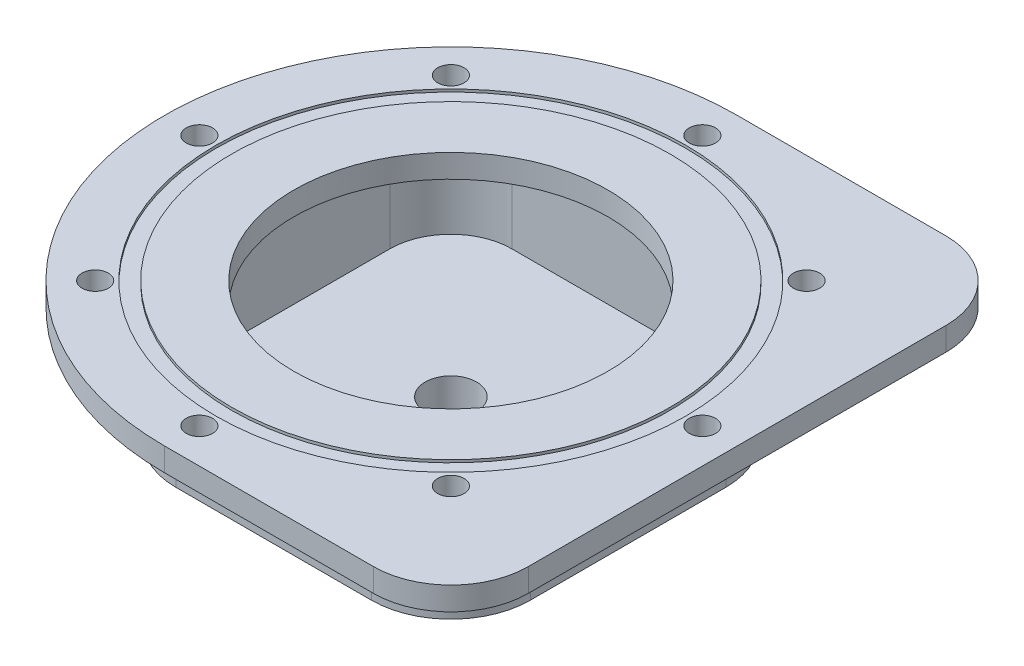
SolidWorks part; units mm, degrees
ref_plane "Front" through (0, 0, 0) normal (0, 0, 1) x (1, 0, 0)
ref_plane "Top" through (0, 0, 0) normal (0, 1, 0) x (1, 0, 0)
ref_plane "Right" through (0, 0, 0) normal (1, 0, 0) x (0, 0, -1)
sketch "Sketch1" plane through (0, 0, 0) normal (0, 1, 0) x (1, 0, 0)
  circle A2 centre (0, 0) radius 38.5318
  circle A3 centre (0, 0) radius 35.9918
  dimension "D1" = 77.0636
  dimension "D2" = 71.9836
sketch "Sketch2" plane through (0, 0, 0) normal (0, 1, 0) x (1, 0, 0)
  line L7 (34.29, 46.99) -> (-34.29, 46.99)
  line L8 (46.99, 34.29) -> (46.99, -34.29)
  line L9 (34.29, -46.99) -> (-34.29, -46.99)
  line L10 (-46.99, 34.29) -> (-46.99, -34.29)
  line L11 (46.99, 46.99) -> (-46.99, -46.99) construction
  line L12 (46.99, -46.99) -> (-46.99, 46.99) construction
  arc A3 (-34.29, -46.99) -> (-46.99, -34.29) centre (-34.29, -34.29) cw
  arc A4 (34.29, 46.99) -> (46.99, 34.29) centre (34.29, 34.29) cw
  arc A5 (46.99, -34.29) -> (34.29, -46.99) centre (34.29, -34.29) cw
  arc A6 (-34.29, 46.99) -> (-46.99, 34.29) centre (-34.29, 34.29) ccw
  circle A12 centre (0, 41.275) radius 2.159
  circle A13 centre (29.1858, 29.1858) radius 2.159
  circle A14 centre (41.275, 0) radius 2.159
  circle A15 centre (29.1858, -29.1858) radius 2.159
  circle A16 centre (0, -41.275) radius 2.159
  circle A17 centre (-29.1858, -29.1858) radius 2.159
  circle A18 centre (-41.275, 0) radius 2.159
  circle A19 centre (-29.1858, 29.1858) radius 2.159
  point P0 (0, 0)
  point P39 (0, 0)
  dimension "D3" = 12.7
  dimension "D4" = 41.275
  dimension "D5" = 4.318
  dimension "D1" = 93.98
  dimension "D2" = 93.98
  dimension "D6" = 8
extrude "Boss-Extrude3" add sketch "Sketch2" against normal blind 3.81
extrude "Cut-Extrude1" cut sketch "Sketch1" against normal blind 0.4445
sketch "Sketch4" plane through (0, 0, 0) normal (0, 1, 0) x (1, 0, 0)
  circle A0 centre (0, 0) radius 25.781
  dimension "D1" = 51.562
extrude "Cut-Extrude2" cut sketch "Sketch4" against normal up to surface (3.81 mm away) up to face at (-29.1858, -3.81, -27.0268)
sketch "Sketch5" plane through (0, -3.81, 0) normal (0, -1, 0) x (1, 0, 0)
  line L0 (-16.035, 29.083) -> (16.035, 29.083)
  line L1 (-16.035, -26.035) -> (16.035, -26.035)
  line L2 (-26.035, -16.035) -> (-26.035, 16.035)
  line L3 (-16.035, 26.035) -> (16.035, 26.035)
  line L4 (26.035, -16.035) -> (26.035, 16.035)
  line L5 (-26.035, -26.035) -> (26.035, 26.035) construction
  line L6 (-26.035, 26.035) -> (26.035, -26.035) construction
  line L7 (29.083, -16.035) -> (29.083, 16.035)
  line L8 (-16.035, -29.083) -> (16.035, -29.083)
  line L9 (-29.083, -16.035) -> (-29.083, 16.035)
  arc A0 (-16.035, -26.035) -> (-26.035, -16.035) centre (-16.035, -16.035) cw
  arc A1 (16.035, -26.035) -> (26.035, -16.035) centre (16.035, -16.035) ccw
  arc A2 (16.035, 26.035) -> (26.035, 16.035) centre (16.035, 16.035) cw
  arc A3 (-26.035, 16.035) -> (-16.035, 26.035) centre (-16.035, 16.035) cw
  arc A4 (16.035, 29.083) -> (29.083, 16.035) centre (16.035, 16.035) cw
  arc A5 (16.035, -29.083) -> (29.083, -16.035) centre (16.035, -16.035) ccw
  arc A6 (-16.035, -29.083) -> (-29.083, -16.035) centre (-16.035, -16.035) cw
  arc A7 (-29.083, 16.035) -> (-16.035, 29.083) centre (-16.035, 16.035) cw
  point P0 (0, 0)
  dimension "D3" = 10
  dimension "D1" = 52.07
  dimension "D2" = 52.07
  dimension "D4" = 3.048
extrude "Boss-Extrude4" add sketch "Sketch5" along normal blind 12.7 contours A7 L9 A6 L8 A5 L7 A4 L0 L2 A3 L3 A2 L4 A1 L1 A0
sketch "Sketch6" plane through (0, -16.51, 0) normal (0, -1, 0) x (1, 0, 0)
  line L4 (-29.083, 16.035) -> (-29.083, -16.035)
  line L5 (-16.035, -29.083) -> (16.035, -29.083)
  line L6 (29.083, -16.035) -> (29.083, 16.035)
  line L7 (16.035, 29.083) -> (-16.035, 29.083)
  line L8 (-29.083, 16.035) -> (-29.083, -16.035)
  line L9 (-16.035, -29.083) -> (16.035, -29.083)
  line L10 (29.083, -16.035) -> (29.083, 16.035)
  line L11 (16.035, 29.083) -> (-16.035, 29.083)
  arc A4 (-16.035, 29.083) -> (-29.083, 16.035) centre (-16.035, 16.035) ccw
  arc A5 (-29.083, -16.035) -> (-16.035, -29.083) centre (-16.035, -16.035) ccw
  arc A6 (16.035, -29.083) -> (29.083, -16.035) centre (16.035, -16.035) ccw
  arc A7 (29.083, 16.035) -> (16.035, 29.083) centre (16.035, 16.035) ccw
  arc A8 (-16.035, 29.083) -> (-29.083, 16.035) centre (-16.035, 16.035) ccw
  arc A9 (-29.083, -16.035) -> (-16.035, -29.083) centre (-16.035, -16.035) ccw
  arc A10 (16.035, -29.083) -> (29.083, -16.035) centre (16.035, -16.035) ccw
  arc A11 (29.083, 16.035) -> (16.035, 29.083) centre (16.035, 16.035) ccw
  dimension "D1" = 0
extrude "Boss-Extrude5" add sketch "Sketch6" along normal blind 6.35
sketch "Sketch7" plane through (0, -3.81, 0) normal (0, -1, 0) x (1, 0, 0)
  line L0 (34.29, -46.99) -> (-34.29, -46.99) construction
  line L1 (-34.29, 46.99) -> (34.29, 46.99) construction
  line L2 (-46.99, 0) -> (-46.99, 46.99)
  line L3 (-46.99, 46.99) -> (0, 46.99)
  line L4 (0, -46.99) -> (-46.99, -46.99)
  line L5 (-46.99, -46.99) -> (-46.99, 0)
  arc A0 (0, -46.99) -> (0, 46.99) centre (0, 0) cw
  arc M18 (-34.29, 46.99) -> (-46.99, 34.29) centre (-34.29, 34.29) ccw
  line M19 (-46.99, 34.29) -> (-46.99, -34.29)
  arc M20 (-46.99, -34.29) -> (-34.29, -46.99) centre (-34.29, -34.29) ccw
  line M21 (-34.29, -46.99) -> (34.29, -46.99)
  line M25 (34.29, 46.99) -> (-34.29, 46.99)
  dimension "D1" = 46.99
extrude "Cut-Extrude3" cut sketch "Sketch7" against normal up to surface (3.81 mm away) contours A0 M19 M25 M18 | A0 M21 M19 M20 up to face at (0, 0, 38.5318)
sketch "Sketch8" plane through (0, 0, 0) normal (1, 0, 0) x (0, 0, -1)
  line L0 (-29.083, -3.81) -> (-29.083, -11.43)
  line L1 (-29.083, -22.86) -> (-29.083, -3.81) construction
  line L2 (-29.083, -11.43) -> (-34.163, -3.81)
  line L3 (-46.99, -3.81) -> (-34.29, -3.81) construction
  line L4 (-34.163, -3.81) -> (-29.083, -3.81)
  dimension "D1" = 5.08
  dimension "D2" = 7.62
extrude "Boss-Extrude6" add sketch "Sketch8" along normal mid plane 31.75
mirror "Mirror1" about plane through (0, 0, 0) normal (0, 0, 1) of "Boss-Extrude6"
sketch "Sketch9" [suppressed] plane through (0, -19.558, 0) normal (0, -1, 0) x (1, 0, 0)
  line L1 (16.035, -16.035) -> (-16.035, -16.035)
  line L2 (16.035, -16.035) -> (16.035, 16.035)
  line L3 (16.035, 16.035) -> (-16.035, 16.035)
  line L4 (-16.035, -16.035) -> (-16.035, 16.035)
  line L5 (16.035, -16.035) -> (-16.035, 16.035) construction
  line L6 (16.035, 16.035) -> (-16.035, -16.035) construction
  circle A0 centre (-16.035, 16.035) radius 1.27
  circle A1 centre (16.035, -16.035) radius 1.27
  point P0 (0, 0)
  dimension "D1" = 2.54
  dimension "D2" = 2.54
hole_wizard "1/8 NPT Tapped Hole1" [suppressed] positions "Sketch10" profile "Sketch11" size "1/8" standard "ANSI Inch"
sketch "Sketch10" [suppressed] plane through (0, -19.558, 0) normal (0, -1, 0) x (-1, 0, 0)
  point P0 (16.035, -16.035)
  point P3 (-16.035, 16.035)
sketch "Sketch11" plane through (-16.035, -19.558, 16.035) normal (1, 0, 0) x (0, 0, -1)
  line L0 (0, 0) -> (0, 5.5805)
  line L1 (4.2164, 3.047) -> (0, 5.5805)
  line L2 (-4.2164, 3.047) -> (0, 5.5805) construction
  line L3 (4.2164, 3.047) -> (4.2164, 6.858)
  line L4 (4.2164, 6.858) -> (4.9362, 6.858)
  line L5 (4.9362, 6.858) -> (5.1415, 0)
  line L6 (-4.9362, 6.858) -> (-5.1415, 0) construction
  line L7 (5.1415, 0) -> (0, 0)
  line L8 (0, -6.35) -> (0, 107.95) construction
  line L11 (-4.2164, 6.858) -> (-4.9362, 6.858) construction
  dimension "Tap Drill Dia." = 8.4328
  dimension "Tap Drill Depth" = 3.047
  dimension "Thread Dia." = 10.283
  dimension "Thread Angle" = 3.43
  dimension "Thread Depth" = 6.858
  dimension "Drill Angle" = 118
sketch "Sketch12" plane through (0, -22.86, 0) normal (0, -1, 0) x (1, 0, 0)
  line L0 (-25.2613, 25.2613) -> (25.2613, -25.2613) construction
  arc A0 (-16.035, 29.083) -> (-29.083, 16.035) centre (-16.035, 16.035) ccw construction
  arc A1 (16.035, -29.083) -> (29.083, -16.035) centre (16.035, -16.035) ccw construction
  circle A2 centre (-16.035, 16.035) radius 4.2164
  circle A3 centre (16.035, -16.035) radius 4.2164
  circle A4 centre (0, 0) radius 4.2164
  dimension "D1" = 8.4328
extrude "Cut-Extrude4" cut sketch "Sketch12" against normal up to next
